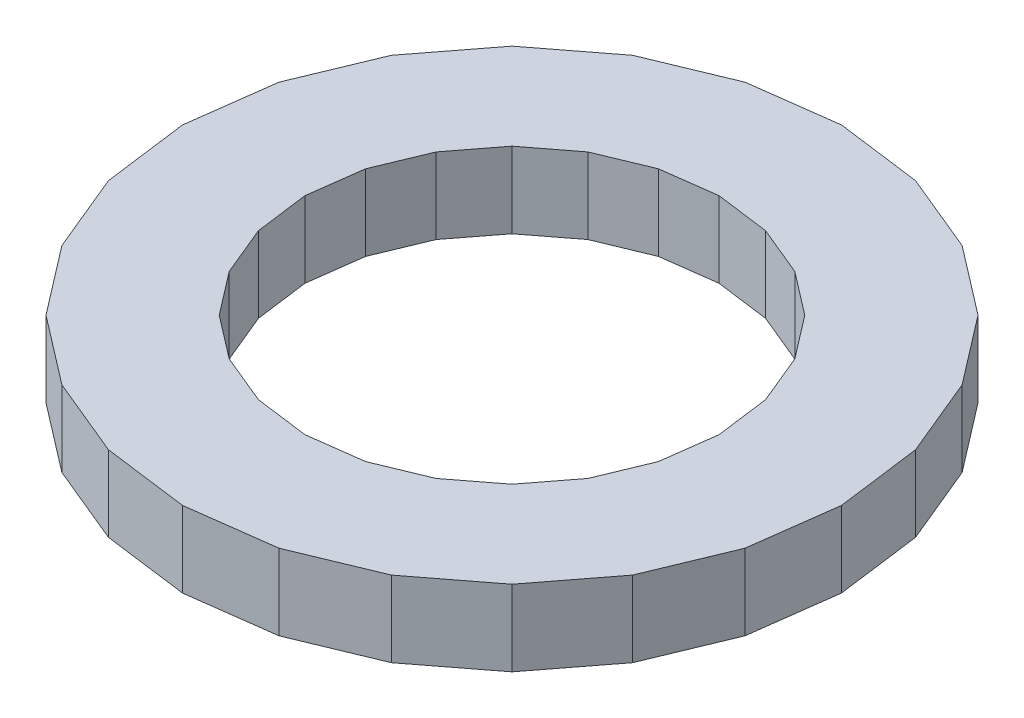
SolidWorks part; units mm, degrees
ref_plane "Front Plane" through (0, 0, 0) normal (0, 0, 1) x (1, 0, 0)
ref_plane "Top Plane" through (0, 0, 0) normal (0, 1, 0) x (1, 0, 0)
ref_plane "Right Plane" through (0, 0, 0) normal (1, 0, 0) x (0, 0, -1)
sketch "Sketch3" plane through (0, 0, 0) normal (0, 1, 0) x (1, 0, 0)
  line L0 (0, 0) -> (-51.9607, 0) construction
  line L1 (-82.7037, 0) -> (-79.8856, -21.4053)
  line L2 (-79.8856, -21.4053) -> (-71.6235, -41.3519)
  line L3 (-71.6235, -41.3519) -> (-58.4804, -58.4804)
  line L4 (-58.4804, -58.4804) -> (-41.3519, -71.6235)
  line L5 (-41.3519, -71.6235) -> (-21.4053, -79.8856)
  line L6 (-21.4053, -79.8856) -> (0, -82.7037)
  line L7 (0, -82.7037) -> (21.4053, -79.8856)
  line L8 (21.4053, -79.8856) -> (41.3519, -71.6235)
  line L9 (41.3519, -71.6235) -> (58.4804, -58.4804)
  line L10 (58.4804, -58.4804) -> (71.6235, -41.3519)
  line L11 (71.6235, -41.3519) -> (79.8856, -21.4053)
  line L12 (79.8856, -21.4053) -> (82.7037, 0)
  line L13 (82.7037, 0) -> (79.8856, 21.4053)
  line L14 (79.8856, 21.4053) -> (71.6235, 41.3519)
  line L15 (71.6235, 41.3519) -> (58.4804, 58.4804)
  line L16 (58.4804, 58.4804) -> (41.3519, 71.6235)
  line L17 (41.3519, 71.6235) -> (21.4053, 79.8856)
  line L18 (21.4053, 79.8856) -> (0, 82.7037)
  line L19 (0, 82.7037) -> (-21.4053, 79.8856)
  line L20 (-21.4053, 79.8856) -> (-41.3519, 71.6235)
  line L21 (-41.3519, 71.6235) -> (-58.4804, 58.4804)
  line L22 (-58.4804, 58.4804) -> (-71.6235, 41.3519)
  line L23 (-71.6235, 41.3519) -> (-79.8856, 21.4053)
  line L24 (-79.8856, 21.4053) -> (-82.7037, 0)
  line L25 (-51.9607, 0) -> (-50.1902, -13.4484)
  line L26 (-50.1902, -13.4484) -> (-44.9993, -25.9803)
  line L27 (-44.9993, -25.9803) -> (-36.7418, -36.7418)
  line L28 (-36.7418, -36.7418) -> (-25.9803, -44.9993)
  line L29 (-25.9803, -44.9993) -> (-13.4484, -50.1902)
  line L30 (-13.4484, -50.1902) -> (0, -51.9607)
  line L31 (0, -51.9607) -> (13.4484, -50.1902)
  line L32 (13.4484, -50.1902) -> (25.9803, -44.9993)
  line L33 (25.9803, -44.9993) -> (36.7418, -36.7418)
  line L34 (36.7418, -36.7418) -> (44.9993, -25.9803)
  line L35 (44.9993, -25.9803) -> (50.1902, -13.4484)
  line L36 (50.1902, -13.4484) -> (51.9607, 0)
  line L37 (51.9607, 0) -> (50.1902, 13.4484)
  line L38 (50.1902, 13.4484) -> (44.9993, 25.9803)
  line L39 (44.9993, 25.9803) -> (36.7418, 36.7418)
  line L40 (36.7418, 36.7418) -> (25.9803, 44.9993)
  line L41 (25.9803, 44.9993) -> (13.4484, 50.1902)
  line L42 (13.4484, 50.1902) -> (0, 51.9607)
  line L43 (0, 51.9607) -> (-13.4484, 50.1902)
  line L44 (-13.4484, 50.1902) -> (-25.9803, 44.9993)
  line L45 (-25.9803, 44.9993) -> (-36.7418, 36.7418)
  line L46 (-36.7418, 36.7418) -> (-44.9993, 25.9803)
  line L47 (-44.9993, 25.9803) -> (-50.1902, 13.4484)
  line L48 (-50.1902, 13.4484) -> (-51.9607, 0)
  line L49 (-82.7037, 0) -> (-51.9607, 0) construction
  circle A0 centre (0, 0) radius 81.9962 construction
  circle A1 centre (0, 0) radius 51.5162 construction
  dimension "D1" = 21.59
  dimension "D2" = 30.48
extrude "Boss-Extrude3" add sketch "Sketch3" along normal blind 19.05
